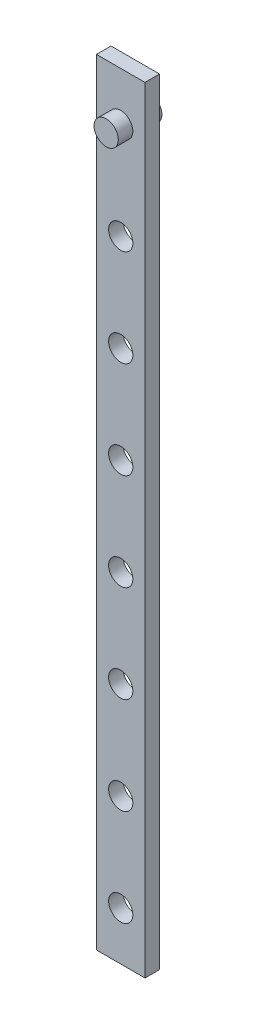
SolidWorks part; units mm, degrees
ref_plane "前基準面" through (0, 0, 0) normal (0, 0, 1) x (1, 0, 0)
ref_plane "上基準面" through (0, 0, 0) normal (0, 1, 0) x (1, 0, 0)
ref_plane "右基準面" through (0, 0, 0) normal (1, 0, 0) x (0, 0, -1)
sketch "草圖1" plane through (0, 0, 0) normal (0, 0, 1) x (1, 0, 0)
  line L0 (0, -80) -> (0, 80) construction
  line L1 (-5, -80) -> (5, -80)
  line L2 (-5, -80) -> (-5, 80)
  line L3 (-5, 80) -> (5, 80)
  line L4 (5, -80) -> (5, 80)
  line L5 (-5, -80) -> (5, 80) construction
  line L6 (-5, 80) -> (5, -80) construction
  circle A0 centre (0, -70) radius 2.5
  circle A1 centre (0, -50) radius 2.5
  circle A2 centre (0, -30) radius 2.5
  circle A3 centre (0, -10) radius 2.5
  circle A4 centre (0, 10) radius 2.5
  circle A5 centre (0, 30) radius 2.5
  circle A6 centre (0, 50) radius 2.5
  point P0 (0, 0)
  dimension "D3" = 10
  dimension "D9" = 5
  dimension "D11" = 5
  dimension "D1" = 160
  dimension "D2" = 10
  dimension "D4" = 20
  dimension "D5" = 20
  dimension "D6" = 20
  dimension "D7" = 20
  dimension "D8" = 20
  dimension "D10" = 20
extrude "填料-伸長1" add sketch "草圖1" along normal blind 3
sketch "草圖2" plane through (0, 0, 3) normal (0, 0, 1) x (1, 0, 0)
  line L1 (5, 80) -> (-5, 80) construction
  circle A0 centre (0, 70) radius 2.5
  dimension "D1" = 5
  dimension "D2" = 10
extrude "填料-伸長2" add sketch "草圖2" along normal blind 3 and the other way blind 6
